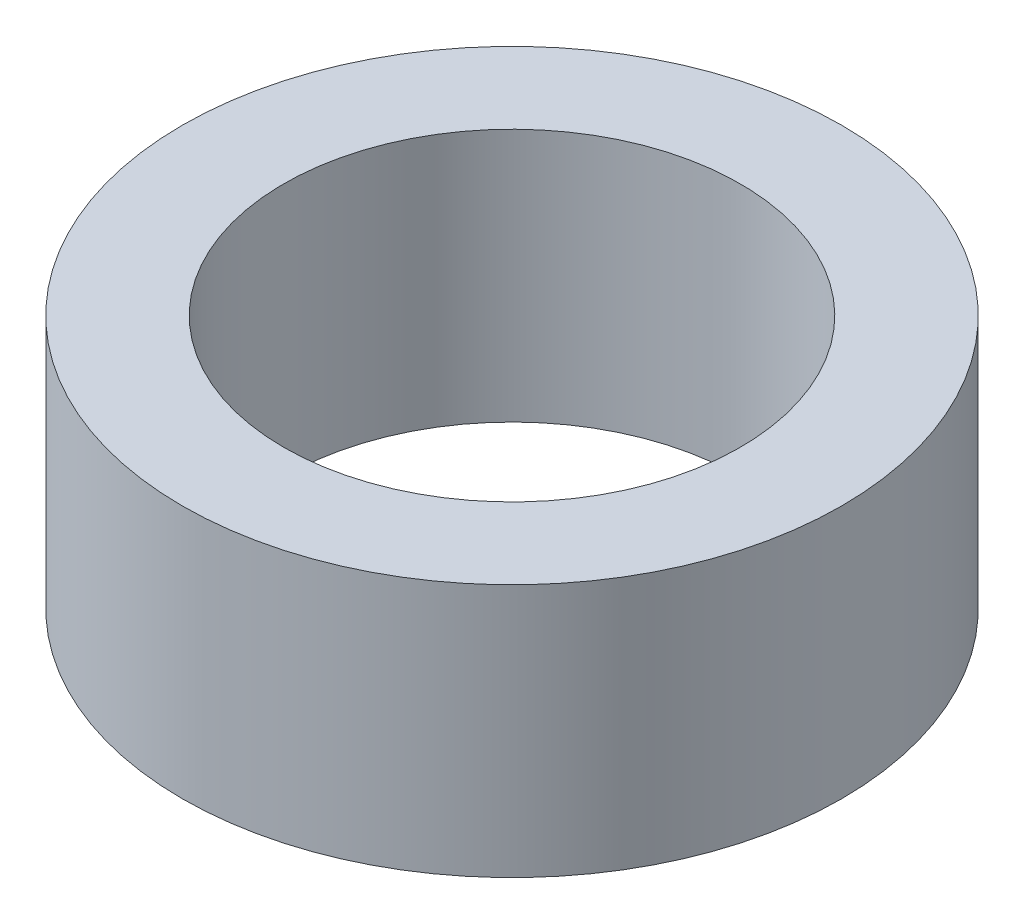
SolidWorks part; units mm, degrees
ref_plane "Front Plane" through (0, 0, 0) normal (0, 0, 1) x (1, 0, 0)
ref_plane "Top Plane" through (0, 0, 0) normal (0, 1, 0) x (1, 0, 0)
ref_plane "Right Plane" through (0, 0, 0) normal (1, 0, 0) x (0, 0, -1)
sketch "Sketch1" plane through (0, 0, 0) normal (0, 1, 0) x (1, 0, 0)
  circle A0 centre (0, 0) radius 6.5
  circle A1 centre (0, 0) radius 4.5
  dimension "D1" = 9
  dimension "D2" = 2
extrude "Boss-Extrude1" add sketch "Sketch1" along normal blind 5
